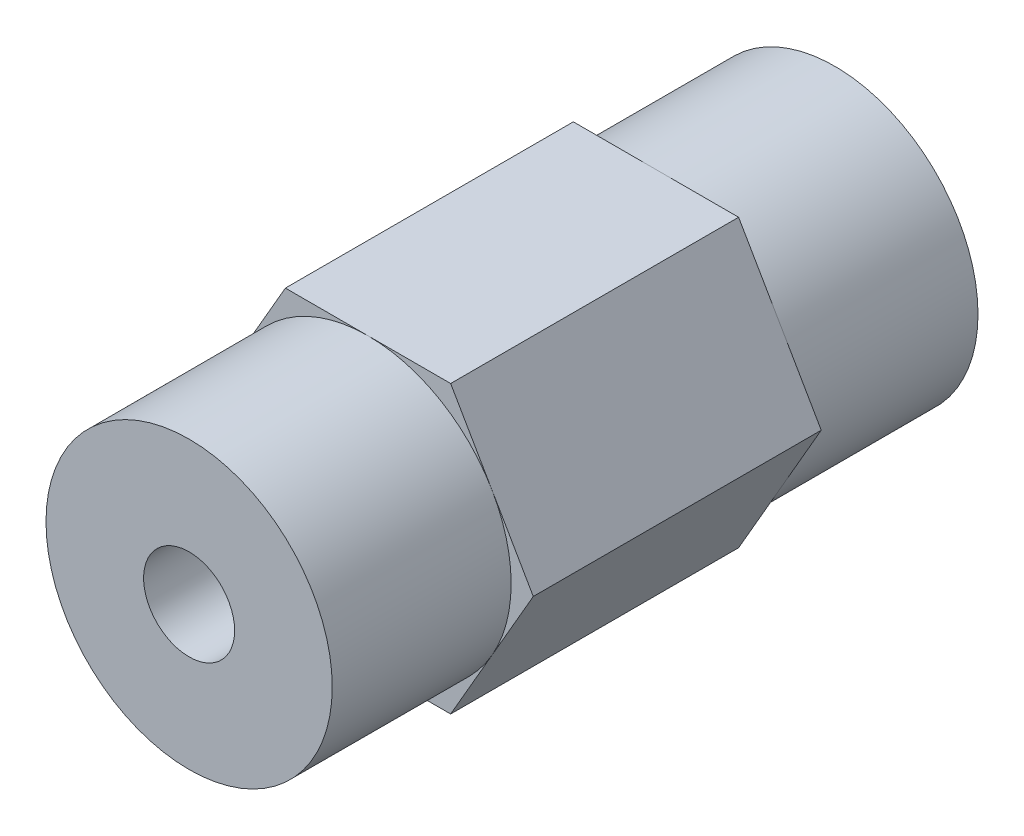
SolidWorks part; units mm, degrees
material "7075-T6 (SN)"
ref_plane "Front Plane" through (0, 0, 0) normal (0, 0, 1) x (1, 0, 0)
ref_plane "Top Plane" through (0, 0, 0) normal (0, 1, 0) x (1, 0, 0)
ref_plane "Right Plane" through (0, 0, 0) normal (1, 0, 0) x (0, 0, -1)
sketch "Sketch1" plane through (0, 0, 0) normal (0, 0, 1) x (1, 0, 0)
  line L1 (7.3323, 0) -> (3.6662, 6.35)
  line L2 (3.6662, 6.35) -> (-3.6662, 6.35)
  line L3 (-3.6662, 6.35) -> (-7.3323, 0)
  line L4 (-7.3323, 0) -> (-3.6662, -6.35)
  line L5 (-3.6662, -6.35) -> (3.6662, -6.35)
  line L6 (3.6662, -6.35) -> (7.3323, 0)
  circle A0 centre (0, 0) radius 6.35 construction
  circle A1 centre (0, 0) radius 2.0193
  dimension "D1" = 12.7
  dimension "D2" = 4.0386
extrude "Boss-Extrude1" add sketch "Sketch1" along normal mid plane 28.6512
hole_wizard "#10-32 Tapped Hole1" positions "3DSketch1" profile "Sketch3" tap size "#10-32" standard "ANSI Inch"
sketch3d "3DSketch1"
  circle A0 centre (0, 0, -14.3256) radius 2.0193 construction
  circle A1 centre (0, 0, 14.3256) radius 2.0193 construction
  point P0 (0, 0, 14.3256)
  point P2 (0, 0, -14.3256)
  point P6 (0, 0, -12.3063)
  point P9 (0, 0, 16.3449)
sketch "Sketch3" plane through (0, 0, 14.3256) normal (1, 0, 0) x (0, -1, 0)
  line L0 (0, 0) -> (0, 13.1513)
  line L1 (0, 13.1513) -> (2.0193, 11.938)
  line L2 (2.0193, 11.938) -> (2.0193, 0)
  line L5 (2.0193, 0) -> (0, 0)
  line L10 (0, 13.1513) -> (-2.0193, 11.938) construction
  line L11 (0, -6.35) -> (0, 107.95) construction
  dimension "Tap Drill Dia." = 4.0386
  dimension "Tap Drill Depth" = 11.938
  dimension "Drill Angle" = 118
cosmetic thread "Hole Thread1" parameters "D1"=9.652, "D2"=4.826
cosmetic thread "Hole Thread2" parameters "D1"=9.652, "D2"=4.826
sketch "Sketch4" plane through (0, 0, 14.3256) normal (0, 0, 1) x (1, 0, 0)
  circle A0 centre (0, 0) radius 6.35
  dimension "D1" = 12.7
extrude "Cut-Extrude-Thin1" cut sketch "Sketch4" against normal blind 7.9375 thin
mirror "Mirror1" about plane through (0, 0, 0) normal (0, 0, 1) of "Cut-Extrude-Thin1"
